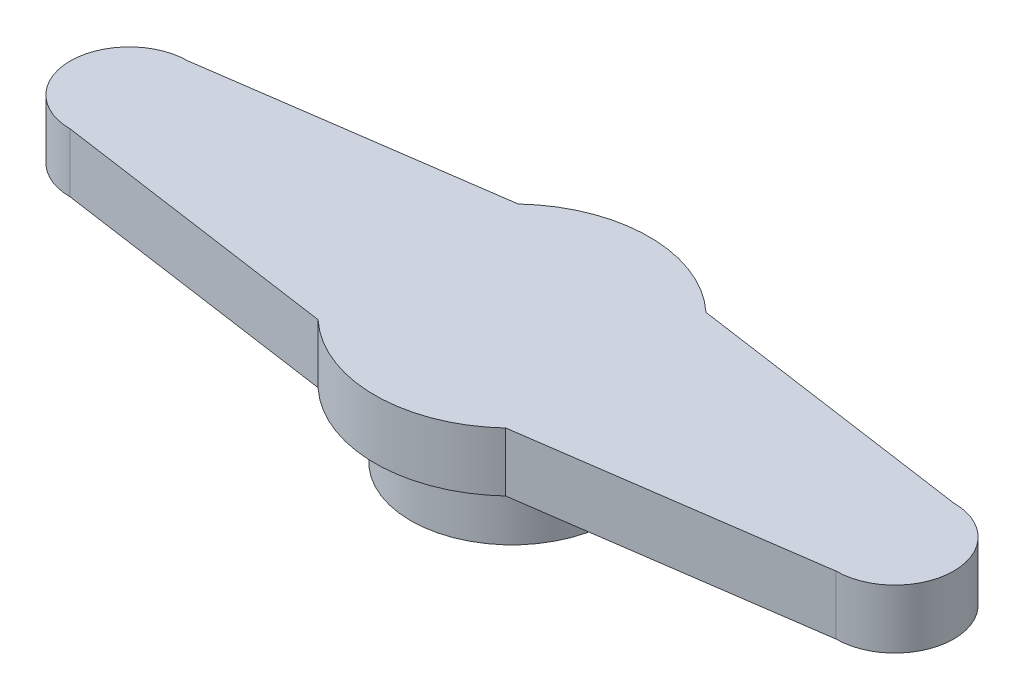
SolidWorks part; units mm, degrees
ref_plane "Front Plane" through (0, 0, 0) normal (0, 0, 1) x (1, 0, 0)
ref_plane "Top Plane" through (0, 0, 0) normal (0, 1, 0) x (1, 0, 0)
ref_plane "Right Plane" through (0, 0, 0) normal (1, 0, 0) x (0, 0, -1)
sketch "Sketch1" plane through (0, 0, 0) normal (0, 1, 0) x (1, 0, 0)
  line L0 (4.0472, 4.318) -> (16.51, 2.54)
  line L1 (4.0472, -4.318) -> (16.51, -2.54)
  line L2 (0, 0) -> (16.51, 0) construction
  line L3 (0, 0) -> (0, 16.8993) construction
  line L4 (-4.0472, -4.318) -> (-16.51, -2.54)
  line L5 (-4.0472, 4.318) -> (-16.51, 2.54)
  arc A0 (-4.0472, -4.318) -> (4.0472, -4.318) centre (0, 0) ccw
  arc A1 (16.51, -2.54) -> (16.51, 2.54) centre (16.51, 0) ccw
  arc A2 (-16.51, -2.54) -> (-16.51, 2.54) centre (-16.51, 0) cw
  arc A3 (4.0472, 4.318) -> (-4.0472, 4.318) centre (0, 0) ccw
  dimension "D1" = 11.8364
  dimension "D2" = 19.05
  dimension "D3" = 5.08
  dimension "D4" = 8.636
extrude "Boss-Extrude1" add sketch "Sketch1" along normal blind 2.54
sketch "Sketch2" plane through (0, 0, 0) normal (0, -1, 0) x (1, 0, 0)
  circle A0 centre (0, 0) radius 4.3688
  dimension "D1" = 8.7376
extrude "Boss-Extrude2" add sketch "Sketch2" along normal blind 2.921
